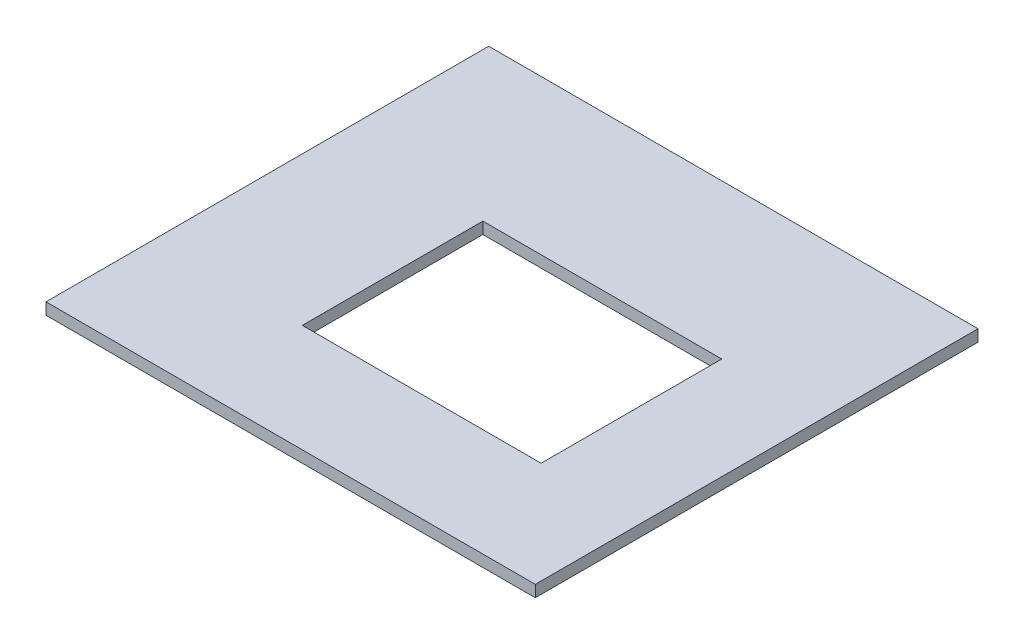
SolidWorks part; units mm, degrees
ref_plane "정면" through (0, 0, 0) normal (0, 0, 1) x (1, 0, 0)
ref_plane "윗면" through (0, 0, 0) normal (0, 1, 0) x (1, 0, 0)
ref_plane "우측면" through (0, 0, 0) normal (1, 0, 0) x (0, 0, -1)
sketch "스케치1" plane through (0, 0, 0) normal (0, 1, 0) x (1, 0, 0)
  line L1 (-21, 19) -> (21, 19)
  line L2 (-21, 19) -> (-21, -19)
  line L3 (-21, -19) -> (21, -19)
  line L4 (21, 19) -> (21, -19)
  line L5 (-21, 19) -> (21, -19) construction
  line L6 (-21, -19) -> (21, 19) construction
  point P0 (0, 0)
  dimension "D1" = 38
  dimension "D2" = 42
extrude "Top" add sketch "스케치1" along normal blind 1
sketch "스케치2" plane through (0, 1, 0) normal (0, 1, 0) x (1, 0, 0)
  line L1 (-8.25, 5.75) -> (12.25, 5.75)
  line L2 (-8.25, 5.75) -> (-8.25, -9.75)
  line L3 (-8.25, -9.75) -> (12.25, -9.75)
  line L4 (12.25, 5.75) -> (12.25, -9.75)
  line L5 (-8.25, 5.75) -> (12.25, -9.75) construction
  line L6 (-8.25, -9.75) -> (12.25, 5.75) construction
  point P0 (2, -2)
  point P5 (3.561, 7.1829)
  point P6 (2.2218, 3.2871)
  point P7 (-2.3436, 3.2262)
  point P8 (2.7088, 3.1654)
  point P9 (3.0741, -0.7913)
  dimension "D1" = 15.5
  dimension "D2" = 20.5
  dimension "D3" = 2
  dimension "D4" = 2
extrude "DHT22_window" cut sketch "스케치2" against normal up to next
